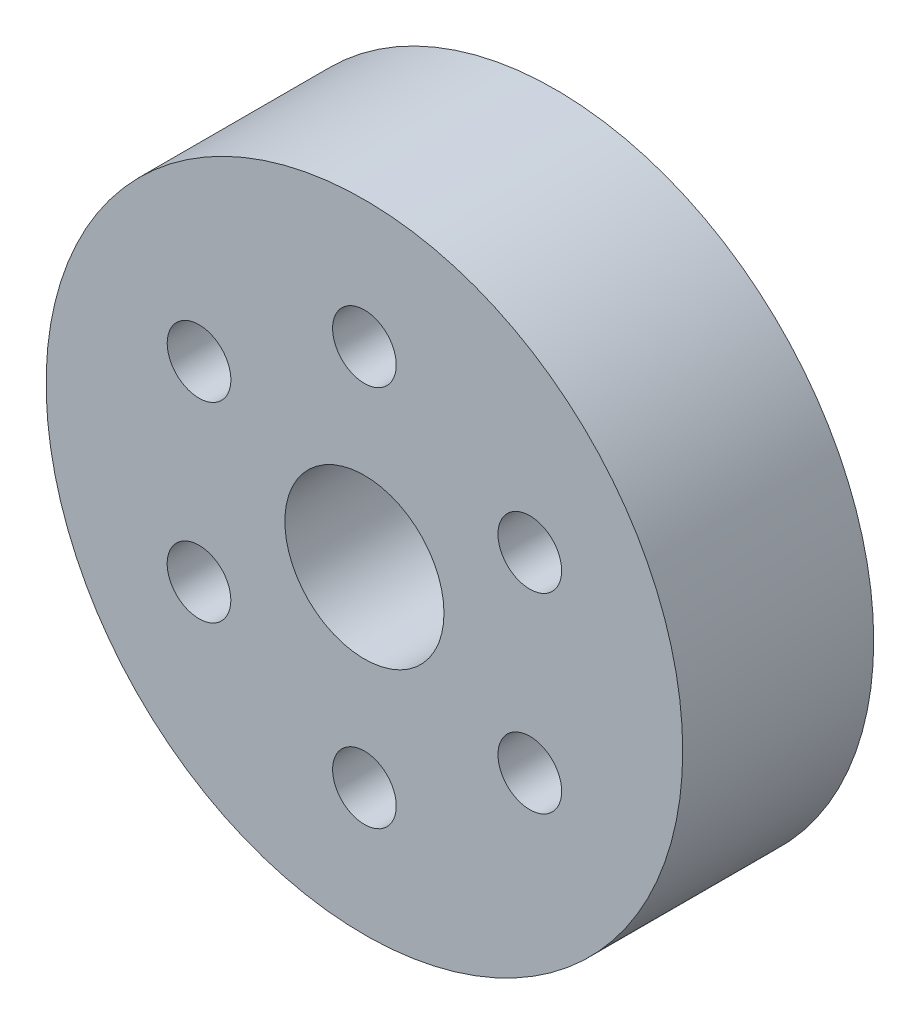
SolidWorks part; units mm, degrees
material "1060 Alloy"
ref_plane "Front Plane" through (0, 0, 0) normal (0, 0, 1) x (1, 0, 0)
ref_plane "Top Plane" through (0, 0, 0) normal (0, 1, 0) x (1, 0, 0)
ref_plane "Right Plane" through (0, 0, 0) normal (1, 0, 0) x (0, 0, -1)
sketch "Sketch2" plane through (0, 0, 0) normal (0, 0, 1) x (1, 0, 0)
  circle A0 centre (0, 0) radius 50
  circle A1 centre (0, 0) radius 12.5
  dimension "D1" = 100
  dimension "D2" = 25
extrude "Boss-Extrude1" add sketch "Sketch2" along normal mid plane 30
sketch "Sketch6" plane through (0, 0, 15) normal (0, 0, 1) x (1, 0, 0)
  line L0 (0, -16.5) -> (0, 16.5) construction
  circle A0 centre (0, 30) radius 5
  circle A1 centre (0, 0) radius 12.5 construction
  dimension "D1" = 30
  dimension "D2" = 10
extrude "Cut-Extrude2" cut sketch "Sketch6" against normal through all
pattern_circular "CirPattern2" count 6 over 360 about axis through (0, 0, 0) along (0, 0, 1) of "Cut-Extrude2"
